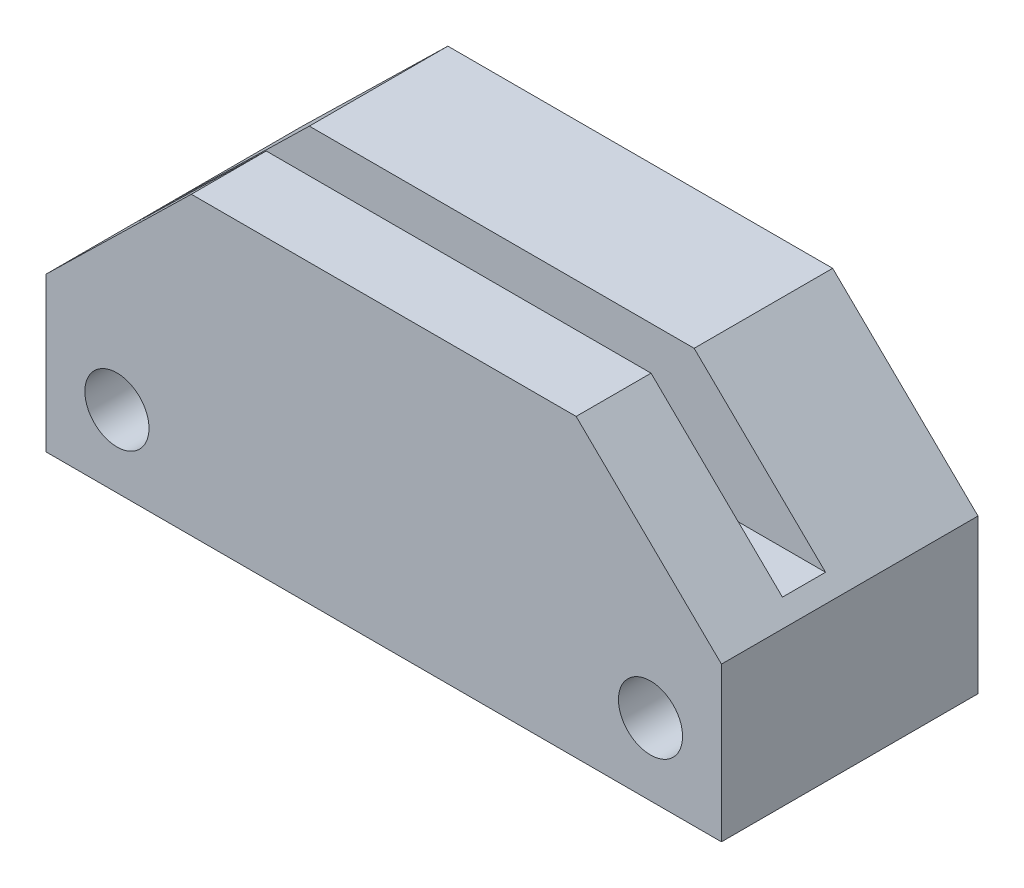
SolidWorks part; units mm, degrees
ref_plane "前视基准面" through (0, 0, 0) normal (0, 0, 1) x (1, 0, 0)
ref_plane "上视基准面" through (0, 0, 0) normal (0, 1, 0) x (1, 0, 0)
ref_plane "右视基准面" through (0, 0, 0) normal (1, 0, 0) x (0, 0, -1)
other "Configuration Table"
sketch "草图1" plane through (0, 0, 0) normal (0, 0, 1) x (1, 0, 0)
  line L0 (0, 0) -> (26.33, 0)
  line L1 (26.33, 0) -> (26.33, 6)
  line L2 (0, 0) -> (0, 6)
  line L3 (13.165, 0) -> (13.165, 14.7896) construction
  line L4 (5.665, 11.53) -> (20.665, 11.53)
  line L5 (0, 6) -> (5.665, 11.53)
  line L6 (20.665, 11.53) -> (26.33, 6)
  dimension "D1" = 26.33
  dimension "D2" = 6
  dimension "D3" = 6
  dimension "D4" = 15
  dimension "D5" = 7.5
  dimension "D6" = 11.53
extrude "凸台-拉伸1" add sketch "草图1" along normal blind 10
sketch "草图2" plane through (0, 11.53, 0) normal (0, 1, 0) x (1, 0, 0)
  line L0 (0, -10) -> (0, 0) construction
  line L1 (0, -5.4) -> (26.33, -5.4)
  line L2 (0, -5.4) -> (0, -7.08)
  line L3 (0, -7.08) -> (26.33, -7.08)
  line L4 (26.33, -5.4) -> (26.33, -7.08)
  line L5 (26.33, -10) -> (26.33, 0) construction
  line L6 (20.665, 0) -> (5.665, 0) construction
  line L7 (5.665, -10) -> (0, -10) construction
  dimension "D1" = 5.4
  dimension "D2" = 2.92
extrude "切除-拉伸1" cut sketch "草图2" against normal blind 5
sketch "草图3" plane through (0, 0, 0) normal (0, 0, -1) x (-1, 0, 0)
  line L0 (-13.165, 0) -> (-13.165, 11.53) construction
  line L1 (0, 0) -> (-26.33, 0) construction
  line L2 (-20.665, 11.53) -> (-5.665, 11.53) construction
  circle A0 centre (-23.565, 2.8) radius 1.25
  circle A1 centre (-2.765, 2.8) radius 1.25
  dimension "D3" = 2.5
  dimension "D4" = 2.5
  dimension "D1" = 20.8
  dimension "D2" = 10.4
  dimension "D5" = 2.8
extrude "切除-拉伸2" cut sketch "草图3" against normal up to next
